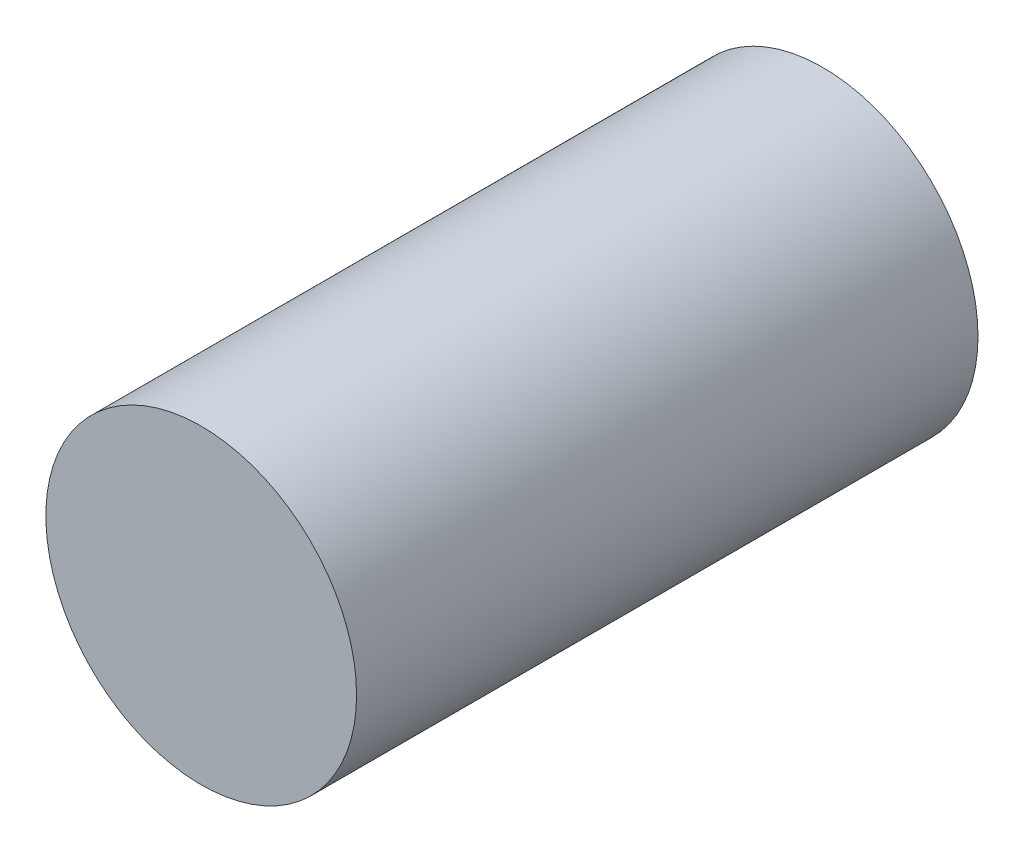
SolidWorks part; units mm, degrees
ref_plane "Plano frontal" through (0, 0, 0) normal (0, 0, 1) x (1, 0, 0)
ref_plane "Plano superior" through (0, 0, 0) normal (0, 1, 0) x (1, 0, 0)
ref_plane "Plano direito" through (0, 0, 0) normal (1, 0, 0) x (0, 0, -1)
sketch "Esboço1" plane through (0, 0, 0) normal (0, 0, 1) x (1, 0, 0)
  circle A0 centre (0, 0) radius 20
extrude "Ressalto-extrusão2" add sketch "Esboço1" along normal blind 80
